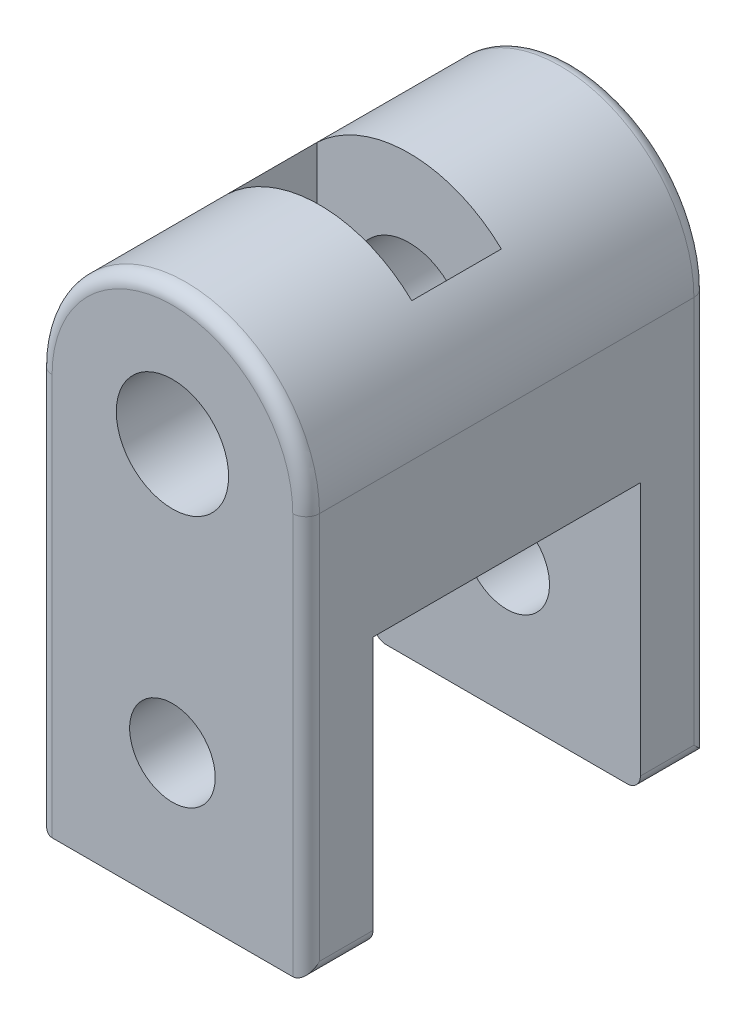
SolidWorks part; units mm, degrees
ref_plane "Front Plane" through (0, 0, 0) normal (0, 0, 1) x (1, 0, 0)
ref_plane "Top Plane" through (0, 0, 0) normal (0, 1, 0) x (1, 0, 0)
ref_plane "Right Plane" through (0, 0, 0) normal (1, 0, 0) x (0, 0, -1)
sketch "Sketch2" plane through (0, 0, 0) normal (0, 0, 1) x (1, 0, 0)
  line L0 (-0.0027, 19.9973) -> (9.9973, 19.9973) construction
  line L1 (-10.0027, -10.0027) -> (9.9973, -10.0027)
  line L2 (-10.0027, -10.0027) -> (-10.0027, 19.9973)
  line L4 (9.9973, -10.0027) -> (9.9973, 19.9973)
  line L5 (-10.0027, -10.0027) -> (9.9973, 9.9973) construction
  line L6 (-10.0027, 10.0082) -> (9.9973, -10.0027) construction
  line L7 (9.9973, 19.9973) -> (-10.0027, 19.9973) construction
  circle A1 centre (-0.0027, 19.9973) radius 4.2
  arc A2 (-10.0027, 19.9973) -> (9.9973, 19.9973) centre (-0.0027, 19.9973) cw
  circle A3 centre (-0.0027, -0.0027) radius 3.2
  point P0 (0, 0)
  point P9 (0, 0)
  dimension "D1" = 20
  dimension "D3" = 8.4
  dimension "D4" = 20
  dimension "D2" = 20
extrude "Boss-Extrude2" add sketch "Sketch2" along normal blind 5
sketch "Sketch3" plane through (0, 0, 0) normal (0, 0, -1) x (-1, 0, 0)
  line L0 (6.9027, 19.2981) -> (6.9027, 27.2354)
  line L1 (0.0027, 12.0298) -> (6.9027, 16.0136)
  line L2 (6.9027, 16.0136) -> (6.9027, 19.2981)
  line L5 (-6.8973, 21.1181) -> (-6.8973, 16.0136)
  line L6 (-6.8973, 16.0136) -> (0.0027, 12.0298)
  line L7 (-6.8973, 21.1181) -> (-6.8973, 27.2354)
  line L8 (7.0986, 23.8679) -> (3.5986, 25.8886) [skipped]
  line L9 (-2.4262, 26.5623) -> (-5.9262, 24.5416) [skipped]
  line L10 (-9.9973, -10.0027) -> (-9.9973, 19.9973) construction
  line L11 (-9.9973, 19.9973) -> (-9.9973, 9.9973)
  line L12 (-9.9973, 9.9973) -> (10.0027, 9.9973)
  line L13 (10.0027, 19.9973) -> (10.0027, -10.0027) construction
  line L14 (10.0027, 9.9973) -> (10.0027, 19.9973)
  line L15 (10.0027, -10.0027) -> (-9.9973, -10.0027) construction
  arc A0 (-6.8973, 19.9973) -> (6.9027, 19.9973) centre (0.0027, 19.9973) ccw construction
  arc A1 (10.0027, 19.9973) -> (-9.9973, 19.9973) centre (0.0027, 19.9973) ccw construction
  arc A2 (-6.8973, 27.2354) -> (-9.9973, 19.9973) centre (0.0027, 19.9973) ccw
  arc A3 (10.0027, 19.9973) -> (6.9027, 27.2354) centre (0.0027, 19.9973) ccw
  dimension "D2" = 20
  dimension "D1" = 13.8
extrude "Boss-Extrude3" add sketch "Sketch3" along normal blind 20
sketch "Sketch4" plane through (0, 0, 0) normal (0, 0, -1) x (-1, 0, 0)
  line L4 (6.9027, 16.0136) -> (6.9027, 27.2354)
  line L5 (-6.8973, 27.2354) -> (-6.8973, 16.0136)
  line L6 (-6.8973, 16.0136) -> (0.0027, 12.0298)
  line L7 (0.0027, 12.0298) -> (6.9027, 16.0136)
  line L8 (6.9027, 16.0136) -> (6.9027, 27.2354)
  line L9 (-6.8973, 27.2354) -> (-6.8973, 16.0136)
  line L10 (-6.8973, 16.0136) -> (0.0027, 12.0298)
  line L11 (0.0027, 12.0298) -> (6.9027, 16.0136)
  circle A0 centre (0.0027, 19.9973) radius 4.2 construction
  arc A1 (6.9027, 27.2354) -> (-6.8973, 27.2354) centre (0.0027, 19.9973) ccw
  arc A2 (6.9027, 27.2354) -> (-6.8973, 27.2354) centre (0.0027, 19.9973) ccw
  circle A3 centre (0.0027, 19.9973) radius 4.2
  dimension "D1" = 0
extrude "Boss-Extrude4" add sketch "Sketch4" along normal blind 6
sketch "Sketch5" plane through (0, 0, -20) normal (0, 0, -1) x (-1, 0, 0)
  line L0 (-9.9973, 19.9973) -> (-9.9973, -10.0027)
  line L1 (-9.9973, -10.0027) -> (10.0027, -10.0027)
  line L2 (10.0027, -10.0027) -> (10.0027, 19.9973)
  circle A0 centre (0.0027, 19.9973) radius 4.2
  arc A1 (-9.9973, 19.9973) -> (10.0027, 19.9973) centre (0.0027, 19.9973) cw
  arc A2 (10.0027, 19.9973) -> (6.9027, 27.2354) centre (0.0027, 19.9973) ccw construction
  circle A3 centre (0.0027, -0.0027) radius 3.2
  line M4 (0.0027, 12.0298) -> (-6.8973, 16.0136)
  line M5 (-6.8973, 16.0136) -> (-6.8973, 27.2354)
  arc M6 (-6.8973, 27.2354) -> (-9.9973, 19.9973) centre (0.0027, 19.9973) ccw
  line M7 (-9.9973, 19.9973) -> (-9.9973, 9.9973)
  line M8 (-9.9973, 9.9973) -> (10.0027, 9.9973)
  line M9 (10.0027, 9.9973) -> (10.0027, 19.9973)
  arc M10 (10.0027, 19.9973) -> (6.9027, 27.2354) centre (0.0027, 19.9973) ccw
  line M11 (6.9027, 27.2354) -> (6.9027, 16.0136)
  line M12 (6.9027, 16.0136) -> (0.0027, 12.0298)
  dimension "D1" = 30
extrude "Boss-Extrude5" add sketch "Sketch5" along normal blind 5 contours M12 M4 M5 M6 M7 M8 M9 M10 M11 | L1 L2 L0 A3 M8 | A1 A0 M5 M4 M12 M11
sketch "Sketch6" plane through (0, 0, -20) normal (0, 0, 1) x (1, 0, 0)
  line L4 (-0.0027, 12.0298) -> (6.8973, 16.0136)
  line L5 (6.8973, 16.0136) -> (6.8973, 27.2354)
  line L6 (-6.9027, 27.2354) -> (-6.9027, 16.0136)
  line L7 (-6.9027, 16.0136) -> (-0.0027, 12.0298)
  line L8 (-0.0027, 12.0298) -> (6.8973, 16.0136)
  line L9 (6.8973, 16.0136) -> (6.8973, 27.2354)
  line L10 (-6.9027, 27.2354) -> (-6.9027, 16.0136)
  line L11 (-6.9027, 16.0136) -> (-0.0027, 12.0298)
  circle A0 centre (-0.0027, 19.9973) radius 4.2 construction
  arc A1 (6.8973, 27.2354) -> (-6.9027, 27.2354) centre (-0.0027, 19.9973) ccw
  arc A2 (6.8973, 27.2354) -> (-6.9027, 27.2354) centre (-0.0027, 19.9973) ccw
  circle A3 centre (-0.0027, 19.9973) radius 4.2
  dimension "D1" = 0
extrude "Boss-Extrude6" add sketch "Sketch6" along normal offset from surface (7.3 mm away) 6.7 up to face at (-0.0027, 20.2579, -6)
fillet "Fillet1" radius 1 10 edges at (9.9973, 4.9973, 5) (-10.0027, 4.9973, 5) (-10.0027, 4.9973, -25) (9.9973, 4.9973, -25) (-0.0027, 29.9973, 5) (-0.0027, 29.9973, -25) (-10.0027, -10.0027, -22.5) (-10.0027, -10.0027, 2.5) (9.9973, -10.0027, 2.5) (9.9973, -10.0027, -22.5)
